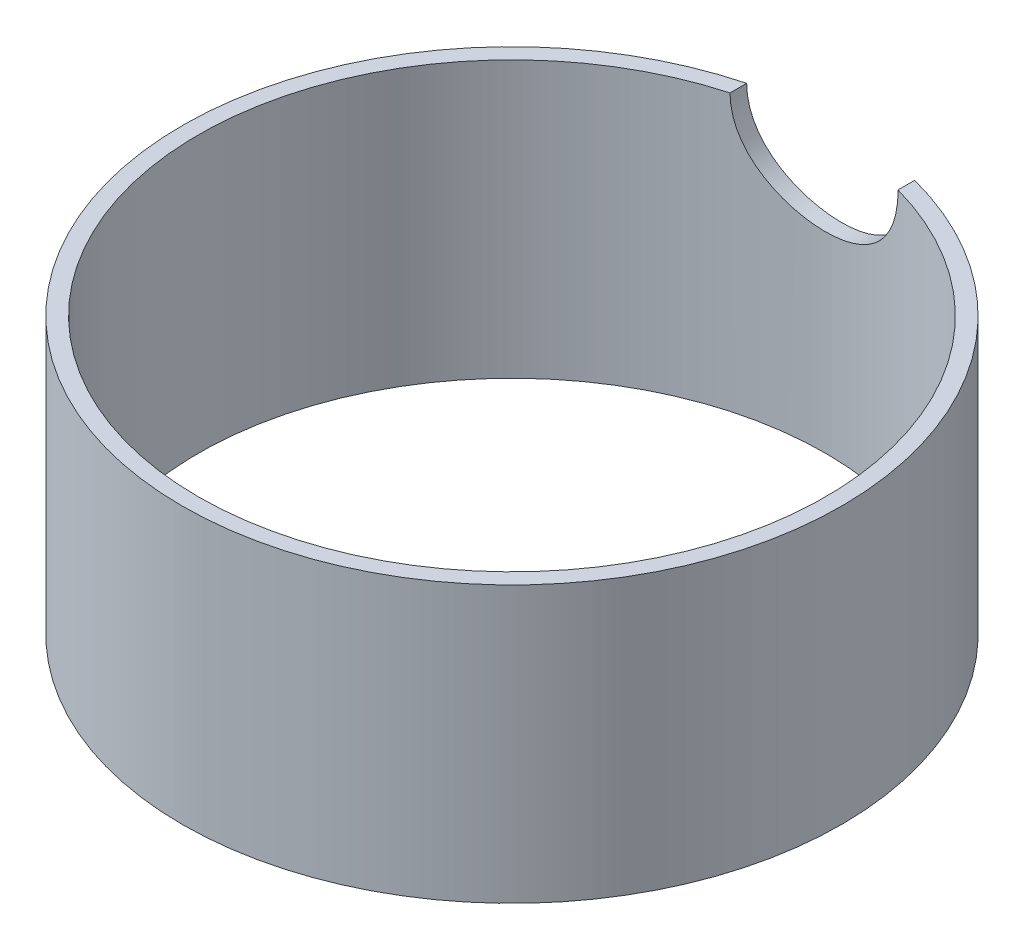
SolidWorks part; units mm, degrees
ref_plane "Front Plane" through (0, 0, 0) normal (0, 0, 1) x (1, 0, 0)
ref_plane "Top Plane" through (0, 0, 0) normal (0, 1, 0) x (1, 0, 0)
ref_plane "Right Plane" through (0, 0, 0) normal (1, 0, 0) x (0, 0, -1)
sketch "Sketch1" plane through (0, 0, 0) normal (0, 1, 0) x (1, 0, 0)
  circle A0 centre (0, 0) radius 41
  circle A1 centre (0, 0) radius 39
  dimension "D1" = 82
  dimension "D2" = 2
extrude "Boss-Extrude1" add sketch "Sketch1" along normal blind 34.3
sketch "Sketch2" plane through (0, 0, 0) normal (0, 0, 1) x (1, 0, 0)
  line L0 (41, 34.3) -> (-41, 34.3) construction
  circle A0 centre (0, 34.3) radius 10.45
  dimension "D1" = 20.9
extrude "Cut-Extrude1" cut sketch "Sketch2" against normal through all
